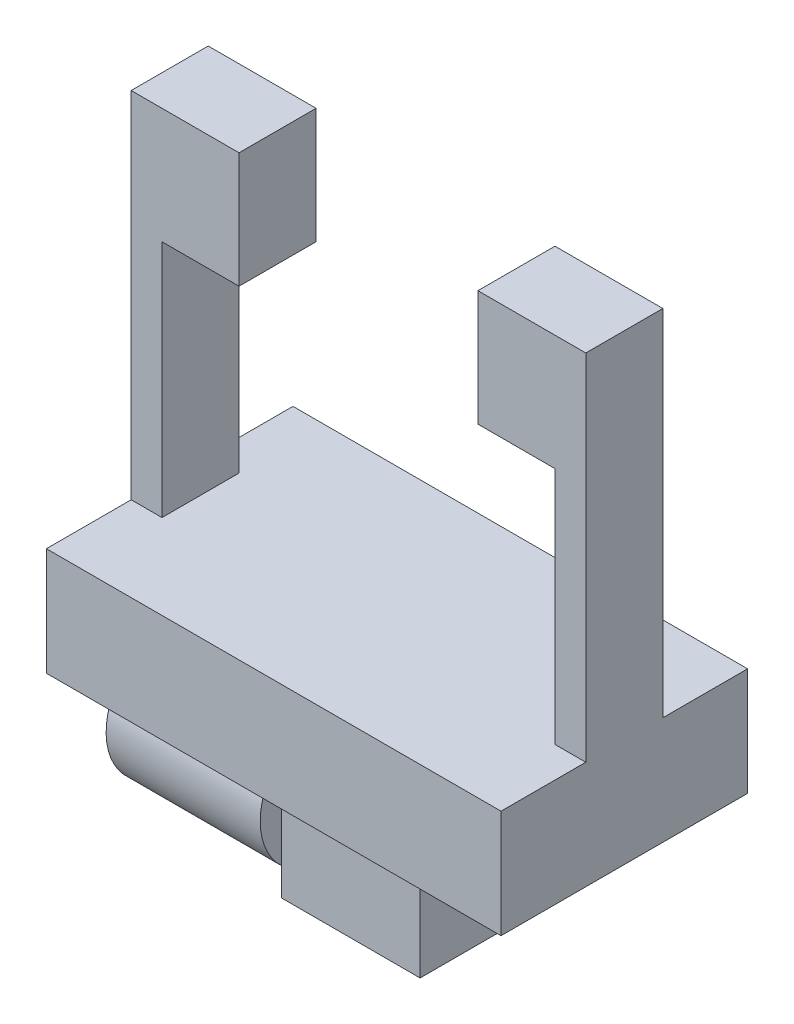
SolidWorks part; units mm, degrees
material "6061-T6 (SS)"
ref_plane "Front Plane" through (0, 0, 0) normal (0, 0, 1) x (1, 0, 0)
ref_plane "Top Plane" through (0, 0, 0) normal (0, 1, 0) x (1, 0, 0)
ref_plane "Right Plane" through (0, 0, 0) normal (1, 0, 0) x (0, 0, -1)
sketch "Sketch1" plane through (0, 0, 0) normal (0, 0, 1) x (1, 0, 0)
  line L1 (-37.465, -8.89) -> (37.465, -8.89)
  line L2 (-37.465, -8.89) -> (-37.465, 8.89)
  line L3 (-37.465, 8.89) -> (37.465, 8.89)
  line L4 (37.465, -8.89) -> (37.465, 8.89)
  line L5 (-37.465, -8.89) -> (37.465, 8.89) construction
  line L6 (-37.465, 8.89) -> (37.465, -8.89) construction
  point P0 (0, 0)
  dimension "D1" = 74.93
  dimension "D2" = 17.78
extrude "Boss-Extrude1" add sketch "Sketch1" along normal mid plane 40.64
sketch "Sketch2" plane through (0, 0, 0) normal (0, 0, 1) x (1, 0, 0)
  line L1 (-37.465, 8.89) -> (-32.385, 8.89)
  line L2 (-37.465, 8.89) -> (-37.465, 48.26)
  line L3 (-37.465, 48.26) -> (-32.385, 48.26)
  line L4 (-32.385, 8.89) -> (-32.385, 48.26)
  line L5 (37.465, 8.89) -> (32.385, 8.89)
  line L6 (37.465, 8.89) -> (37.465, 48.26)
  line L7 (37.465, 48.26) -> (32.385, 48.26)
  line L8 (32.385, 8.89) -> (32.385, 48.26)
  dimension "D1" = 5.08
  dimension "D2" = 39.37
  dimension "D3" = 5.08
  dimension "D4" = 39.37
extrude "Boss-Extrude2" add sketch "Sketch2" along normal mid plane 12.7
sketch "Sketch3" plane through (0, 0, 0) normal (0, 0, 1) x (1, 0, 0)
  line L1 (37.465, 48.26) -> (19.685, 48.26)
  line L2 (37.465, 48.26) -> (37.465, 67.31)
  line L3 (37.465, 67.31) -> (19.685, 67.31)
  line L4 (19.685, 48.26) -> (19.685, 67.31)
  line L5 (-37.465, 48.26) -> (-19.685, 48.26)
  line L6 (-37.465, 48.26) -> (-37.465, 67.31)
  line L7 (-37.465, 67.31) -> (-19.685, 67.31)
  line L8 (-19.685, 48.26) -> (-19.685, 67.31)
  dimension "D1" = 17.78
  dimension "D2" = 19.05
  dimension "D3" = 17.78
  dimension "D4" = 19.05
extrude "Boss-Extrude3" add sketch "Sketch3" along normal mid plane 12.7
sketch "Sketch5" plane through (0, 0, 0) normal (0, 0, 1) x (1, 0, 0)
  line L0 (-37.465, -8.89) -> (37.465, -8.89) construction
  line L1 (-11.43, -8.89) -> (11.43, -8.89)
  line L2 (-11.43, -8.89) -> (-11.43, -34.29)
  line L3 (-11.43, -34.29) -> (11.43, -34.29)
  line L4 (11.43, -8.89) -> (11.43, -34.29)
  point P4 (0, -8.89)
  dimension "D1" = 22.86
  dimension "D2" = 25.4
extrude "Boss-Extrude4" add sketch "Sketch5" along normal mid plane 15.24
sketch "Sketch6" plane through (-11.43, 0, 0) normal (-1, 0, 0) x (0, 0, 1)
  line L0 (-7.62, -8.89) -> (7.62, -34.29) construction
  circle A0 centre (0, -21.59) radius 11.1125
  dimension "D1" = 22.225
extrude "Boss-Extrude5" add sketch "Sketch6" along normal blind 25.4
equation "\"Base Length\"= 2.95in"
equation "\"Base Height\" = 0.7in"
equation "\"Support Width\"= 0.2in"
equation "\"Support Height\" = 1.55in"
equation "\"Lip Width\"= 0.7in"
equation "\"Lip Height\"= 0.75in"
equation "\"Stem Height\"= 1in"
equation "\"Stem Width\"= 0.9in"
equation "\"Bar Diameter\" = \"Min Bar Diameter\" + \"Diameter Allow\""
equation "\"D1@Sketch1\"=\"Base Length\""
equation "\"D2@Sketch1\"=\"Base Height\""
equation "\"D1@Sketch2\"=\"Support Width\""
equation "\"D3@Sketch2\"=\"Support Width\""
equation "\"D2@Sketch2\"=\"Support Height\""
equation "\"D4@Sketch2\"=\"Support Height\""
equation "\"D3@Sketch3\"=\"Lip Width\""
equation "\"D1@Sketch3\"=\"Lip Width\""
equation "\"D4@Sketch3\"=\"Lip Height\""
equation "\"D2@Sketch3\"=\"Lip Height\""
equation "\"D1@Sketch5\"=\"Stem Width\""
equation "\"D2@Sketch5\"=\"Stem Height\""
equation "\"D1@Sketch6\"=\"Bar Diameter\""
equation "\"Base Depth\"= 1.6in"
equation "\"D1@Boss-Extrude1\"=\"Base Depth\""
equation "\"Support Depth\"= 0.5in"
equation "\"D1@Boss-Extrude2\"=\"Support Depth\""
equation "\"Lip Depth\"= 0.5in"
equation "\"D1@Boss-Extrude3\"=\"Lip Depth\""
equation "\"Stem Depth\"= 0.6in"
equation "\"D1@Boss-Extrude4\"=\"Stem Depth\""
equation "\"Bar Length\"= 1in"
equation "\"D1@Boss-Extrude5\"=\"Bar Length\""
equation "\"Bar Moment\"= 600"
equation "\"Stress Allow\"= 10000"
equation "\"Min Bar Diameter\"= ( 32 * \"Bar Moment\" / ( 3.14 * \"Stress Allow\" ) ) ^ ( 1 / 3 ) * ( 1in )"
equation "\"Diameter Allow\"= 0.875in - ( 32 * 600 / ( 3.14 * 10000 ) ) ^ ( 1 / 3 ) * 1in"
